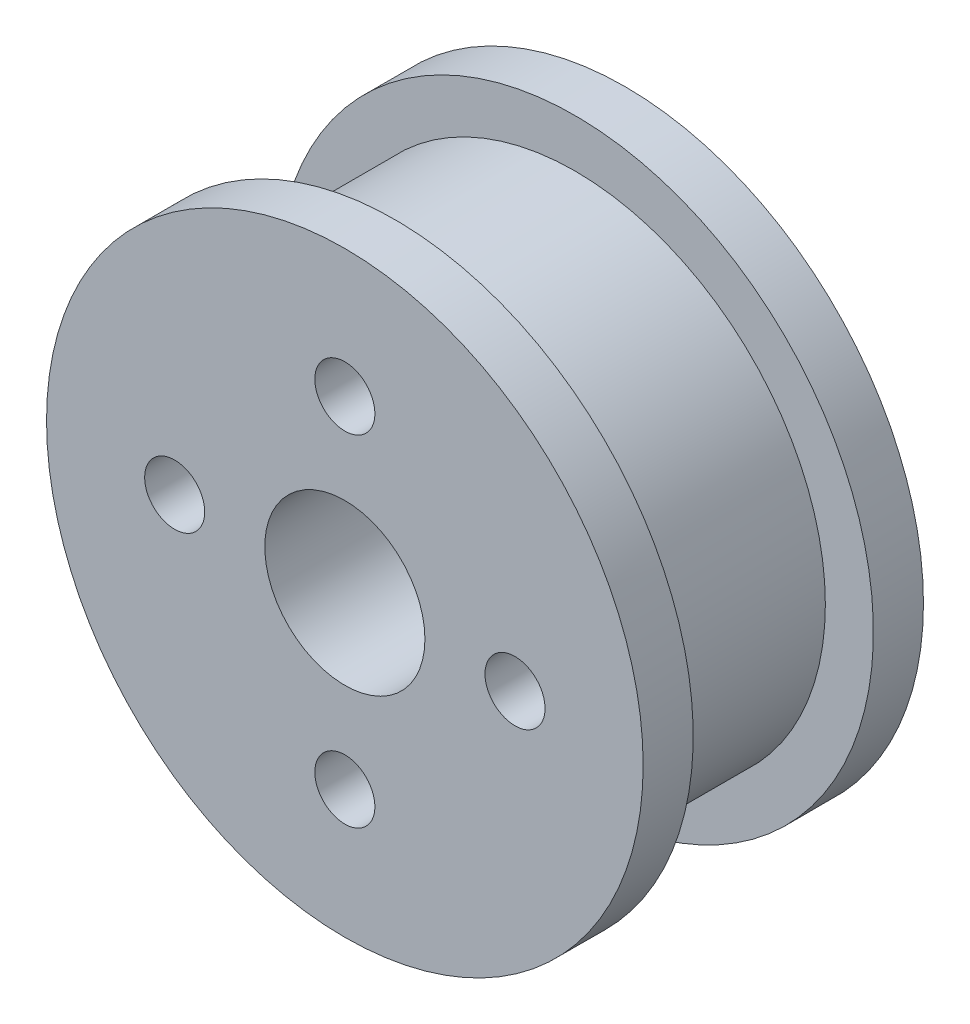
SolidWorks part; units mm, degrees
ref_plane "Front Plane" through (0, 0, 0) normal (0, 0, 1) x (1, 0, 0)
ref_plane "Top Plane" through (0, 0, 0) normal (0, 1, 0) x (1, 0, 0)
ref_plane "Right Plane" through (0, 0, 0) normal (1, 0, 0) x (0, 0, -1)
sketch "Sketch1" plane through (0, 0, 0) normal (0, 0, 1) x (1, 0, 0)
  circle A0 centre (0, 0) radius 14.9
  circle A1 centre (0, 0) radius 4
  dimension "D1" = 29.8
  dimension "D2" = 8
extrude "Boss-Extrude1" add sketch "Sketch1" along normal blind 14
ref_plane "Plane1" through (0, 0, 2.5) normal (0, 0, -1) x (-1, 0, 0)
sketch "Sketch2" plane through (0, 0, 2.5) normal (0, 0, -1) x (-1, 0, 0)
  circle A0 centre (0, 0) radius 12.5
  circle A1 centre (0, 0) radius 14.9
  dimension "D1" = 25
extrude "Cut-Extrude1" cut sketch "Sketch2" against normal blind 9
sketch "Sketch3" plane through (0, 0, 0) normal (0, 0, -1) x (-1, 0, 0)
  circle A1 centre (0, 0) radius 4.5 construction
  circle A2 centre (0, 0) radius 12.5 construction
  circle A3 centre (0, 0) radius 14.9 construction
  circle A4 centre (0, 0) radius 8.5
  circle A5 centre (0, 8.5) radius 1.5
  circle A6 centre (8.5, 0) radius 1.5
  circle A7 centre (0, -8.5) radius 1.5
  circle A8 centre (-8.5, 0) radius 1.5
  dimension "D1" = 9
  dimension "D2" = 2.4
  dimension "D3" = 17
  dimension "D4" = 3
  dimension "D5" = 3
  dimension "D6" = 3
  dimension "D7" = 3
extrude "Cut-Extrude2" cut sketch "Sketch3" against normal through all contours A4 A5 | A4 A5 | A4 A8 | A4 A8 | A4 A6 | A4 A6 | A4 A7 | A4 A7
